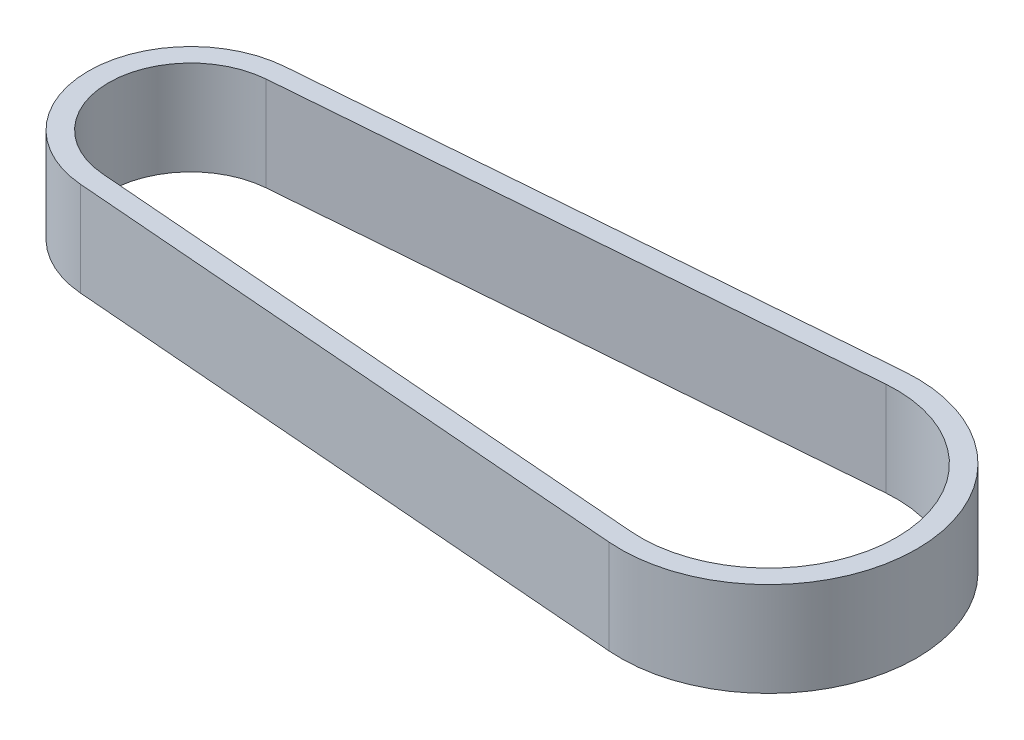
SolidWorks part; units mm, degrees
ref_plane "Front Plane" through (0, 0, 0) normal (0, 0, 1) x (1, 0, 0)
ref_plane "Top Plane" through (0, 0, 0) normal (0, 1, 0) x (1, 0, 0)
ref_plane "Right Plane" through (0, 0, 0) normal (1, 0, 0) x (0, 0, -1)
sketch "Sketch1" plane through (0, 0, 0) normal (0, 1, 0) x (1, 0, 0)
  line L0 (0, 0) -> (42.9, 0) construction
  line L1 (-0.4834, 6.0808) -> (42.1471, 9.4701)
  line L2 (-0.4834, -6.0808) -> (42.1471, -9.4701)
  line L3 (-0.6023, 7.5761) -> (42.0282, 10.9654)
  line L4 (-0.6023, -7.5761) -> (42.0282, -10.9654)
  arc A0 (-0.4834, 6.0808) -> (-0.4834, -6.0808) centre (0, 0) ccw
  arc A1 (42.1471, -9.4701) -> (42.1471, 9.4701) centre (42.9, 0) ccw
  arc A2 (42.0282, -10.9654) -> (42.0282, 10.9654) centre (42.9, 0) ccw
  arc A3 (-0.6023, 7.5761) -> (-0.6023, -7.5761) centre (0, 0) ccw
  dimension "D1" = 12.2
  dimension "D2" = 19
  dimension "D3" = 1.5
  dimension "D4" = 42.9
extrude "Boss-Extrude1" add sketch "Sketch1" along normal blind 7
